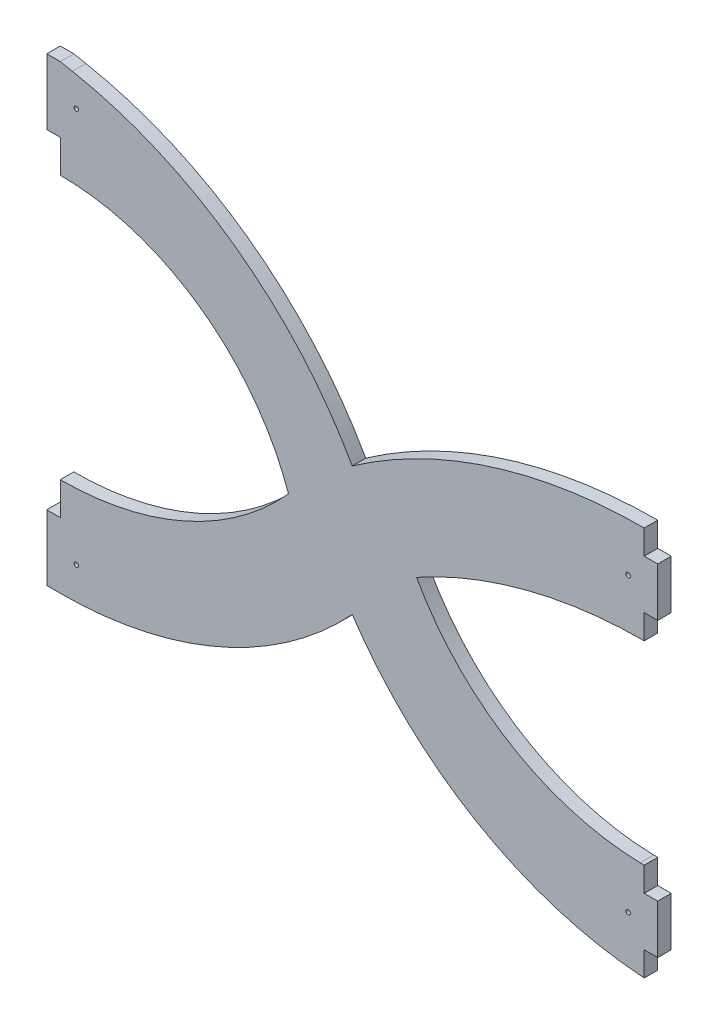
SolidWorks part; units mm, degrees
ref_plane "Front Plane" through (0, 0, 0) normal (0, 0, 1) x (1, 0, 0)
ref_plane "Top Plane" through (0, 0, 0) normal (0, 1, 0) x (1, 0, 0)
ref_plane "Right Plane" through (0, 0, 0) normal (1, 0, 0) x (0, 0, -1)
sketch "Sketch1" plane through (0, 0, 0) normal (0, 0, 1) x (1, 0, 0)
  line L1 (-141.9798, 90.4351) -> (99.3202, 90.4351)
  line L2 (-141.9798, 90.4351) -> (-141.9798, -107.6849)
  line L3 (-141.9798, -107.6849) -> (99.3202, -107.6849)
  line L4 (99.3202, 90.4351) -> (99.3202, -107.6849)
  dimension "D1" = 241.3
  dimension "D2" = 198.12
extrude "Boss-Extrude1" add sketch "Sketch1" along normal blind 5.334
sketch "Sketch2" plane through (0, 0, 5.334) normal (0, 0, 1) x (1, 0, 0)
  line L0 (99.3202, -107.6849) -> (99.3202, 90.4351) construction
  line L1 (99.3202, -107.6849) -> (93.9862, -107.6849)
  line L2 (99.3202, -107.6849) -> (99.3202, -98.0329)
  line L3 (99.3202, -98.0329) -> (93.9862, -98.0329)
  line L4 (93.9862, -107.6849) -> (93.9862, -98.0329)
  line L5 (99.3202, -78.7289) -> (93.9862, -78.7289)
  line L7 (93.9862, 17.2831) -> (99.3202, 17.2831)
  line L8 (93.9862, 17.2831) -> (93.9862, -78.7289)
  line L9 (93.9862, 36.5871) -> (93.9862, 17.2831) construction
  line L10 (99.3202, 90.4351) -> (93.9862, 90.4351)
  line L11 (99.3202, 90.4351) -> (99.3202, 36.5871)
  line L12 (99.3202, 36.5871) -> (93.9862, 36.5871)
  line L13 (93.9862, 90.4351) -> (93.9862, 36.5871)
  line L16 (99.3202, 17.2831) -> (99.3202, -78.7289)
  line L18 (93.9862, -78.7289) -> (93.9862, -98.0329) construction
  dimension "D1" = 5.334
  dimension "D3" = 19.304
  dimension "D4" = 9.652
  dimension "D5" = 19.304
  dimension "D2" = 96.012
extrude "Cut-Extrude1" cut sketch "Sketch2" against normal through all
sketch "Sketch3" plane through (0, 0, 5.334) normal (0, 0, 1) x (1, 0, 0)
  line L1 (-141.9798, -107.6849) -> (-136.6458, -107.6849)
  line L2 (-141.9798, -107.6849) -> (-141.9798, -91.4289)
  line L3 (-141.9798, -91.4289) -> (-136.6458, -91.4289)
  line L4 (-136.6458, -107.6849) -> (-136.6458, -91.4289)
  line L5 (-141.9798, 90.4351) -> (-141.9798, -107.6849) construction
  line L6 (-136.6458, -65.5209) -> (-141.9798, -65.5209)
  line L7 (-136.6458, -65.5209) -> (-136.6458, 64.5271)
  line L8 (-136.6458, 64.5271) -> (-141.9798, 64.5271)
  line L9 (-141.9798, -65.5209) -> (-141.9798, 64.5271)
  line L10 (-136.6458, -65.5209) -> (-136.6458, -91.4289) construction
  line L11 (-136.6458, 64.5271) -> (-136.6458, 90.4351) construction
  line L12 (93.9862, 90.4351) -> (-141.9798, 90.4351) construction
  dimension "D1" = 16.256
  dimension "D2" = 25.908
  dimension "D3" = 25.908
  dimension "D4" = 5.334
extrude "Cut-Extrude2" cut sketch "Sketch3" against normal through all
sketch "Sketch5" plane through (0, 0, 5.334) normal (0, 0, 1) x (1, 0, 0)
  line L0 (-136.6458, -91.4289) -> (93.9862, -107.6849) construction
  line L1 (-136.6458, -91.4289) -> (93.9862, -107.6849)
  line L2 (-136.6458, -91.4289) -> (-136.6458, -146.6044)
  line L3 (93.9862, -107.6849) -> (93.9862, -162.8604)
  line L4 (-136.6458, -146.6044) -> (93.9862, -162.8604)
extrude "Cut-Extrude5" cut sketch "Sketch5" against normal through all
sketch "Sketch6" plane through (0, 0, 5.334) normal (0, 0, 1) x (1, 0, 0)
  line L0 (-136.6458, 64.5271) -> (-136.6458, 90.4351) construction
  line L1 (93.9862, 90.4351) -> (-141.9798, 90.4351) construction
  line L2 (93.9862, 36.5871) -> (93.9862, 46.2391) construction
  line L3 (93.9862, 90.4351) -> (93.9862, 36.5871) construction
  line L4 (-136.6458, 90.4351) -> (93.9862, 46.2391)
  line L5 (-136.6458, 90.4351) -> (-136.6458, 134.6311)
  line L6 (93.9862, 46.2391) -> (93.9862, 90.4351)
  line L7 (-136.6458, 134.6311) -> (93.9862, 90.4351)
  dimension "D1" = 9.652
extrude "Cut-Extrude6" cut sketch "Sketch6" against normal through all
sketch "Sketch7" plane through (0, 0, 5.334) normal (0, 0, 1) x (1, 0, 0)
  line L0 (-21.3298, 68.3371) -> (-21.3298, -99.5569) construction
  line L1 (-136.6458, 90.4351) -> (93.9862, 46.2391) construction
  line L2 (93.9862, -107.6849) -> (-136.6458, -91.4289) construction
  line L3 (93.9862, -30.7229) -> (-136.6458, -0.4969) construction
  line L4 (93.9862, 17.2831) -> (93.9862, -78.7289) construction
  line L5 (-136.6458, -65.5209) -> (-136.6458, 64.5271) construction
  line L6 (-136.6458, 64.5271) -> (-136.6458, 51.5731) construction
  line L7 (-136.6458, -65.5209) -> (-136.6458, -52.5669) construction
  line L8 (93.9862, 17.2831) -> (93.9862, 7.6311) construction
  line L9 (93.9862, -78.7289) -> (93.9862, -69.0769) construction
  line L10 (-136.6458, 64.5271) -> (-131.8569, 89.5174) construction
  line L11 (93.9862, 36.5871) -> (93.9862, 46.2391) construction
  line L12 (-131.8569, 89.5174) -> (93.9862, 46.2391)
  line L13 (-136.6458, -65.5209) -> (-136.6458, -91.4289) construction
  line L14 (93.9862, -98.0329) -> (93.3092, -107.6372) construction
  line L15 (-136.6458, -91.4289) -> (93.3092, -107.6372)
  circle A0 centre (-21.3298, -15.6099) radius 25.4 construction
  arc A1 (93.9862, 7.6311) -> (4.0702, -15.6099) centre (93.9862, -177.9253) ccw
  arc A2 (4.0702, -15.6099) -> (92.3478, -69.0769) centre (94.8631, 34.6856) ccw
  arc A3 (92.3478, -69.0769) -> (93.9862, 7.6311) centre (93.2775, -30.7253) ccw
  arc A4 (-136.6458, 51.5731) -> (-46.5144, -12.3093) centre (-136.6458, -43.9511) cw
  arc A5 (-136.6458, -52.5669) -> (-46.5144, -12.3093) centre (-136.6458, 68.4578) ccw
  arc A6 (-136.6458, 51.5731) -> (-136.6458, -52.5669) centre (-136.6458, -0.4969) ccw
  arc A7 (-131.8569, 89.5174) -> (-21.3298, 9.7901) centre (-162.2521, -69.0963) cw
  arc A8 (93.9862, 46.2391) -> (-21.3298, 9.7901) centre (93.9862, -154.4017) ccw
  arc A9 (-136.6458, -91.4289) -> (-21.3298, -41.0099) centre (-136.6458, 65.6533) ccw
  arc A10 (93.3092, -107.6372) -> (-21.3298, -41.0099) centre (103.8923, 42.5098) cw
extrude "Cut-Extrude7" cut sketch "Sketch7" against normal through all
sketch "Sketch8" plane through (0, 0, 5.334) normal (0, 0, 1) x (1, 0, 0)
  line L0 (-141.9798, 90.4351) -> (-141.9798, 64.5271) construction
  line L1 (-141.9798, 77.4811) -> (-82.7249, 77.4811) construction
  line L2 (-141.9798, 77.4811) -> (-141.9798, -78.4749) construction
  line L3 (-141.9798, -65.5209) -> (-141.9798, -91.4289) construction
  line L4 (-141.9798, -0.4969) -> (-61.4833, -0.4969) construction
  circle A0 centre (-130.2958, 77.4811) radius 0.889
  circle A1 centre (-130.2958, -78.4749) radius 0.889
  point P2 (-141.9798, 77.4811)
  dimension "D3" = 1.778
  dimension "D1" = 11.684
  dimension "D2" = 0
extrude "Cut-Extrude8" cut sketch "Sketch8" against normal through all
sketch "Sketch9" plane through (0, 0, 5.334) normal (0, 0, 1) x (1, 0, 0)
  line L0 (99.3202, 26.9351) -> (60.8503, 26.9351) construction
  line L1 (99.3202, 17.2831) -> (99.3202, 36.5871) construction
  line L2 (99.3202, -88.3809) -> (53.0576, -88.3809) construction
  line L3 (99.3202, -98.0329) -> (99.3202, -78.7289) construction
  line L4 (99.3202, 26.9351) -> (99.3202, -88.3809) construction
  line L5 (99.3202, -30.7229) -> (41.8715, -30.7229) construction
  line L6 (93.9862, 46.2391) -> (93.9862, 36.5871) construction
  circle A0 centre (87.6362, 26.9351) radius 0.889
  circle A1 centre (87.6362, -88.3809) radius 0.889
  dimension "D1" = 1.778
  dimension "D2" = 0
  dimension "D3" = 6.35
extrude "Cut-Extrude9" cut sketch "Sketch9" against normal through all
equation "\"MDF\"= .21in"
equation "\"Foamcore\"= .13in"
equation "\"Gmaterial\"= \"MDF\""
equation "\"D1@Boss-Extrude1\"=\"MDF\""
equation "\"D1@Sketch2\"=\"MDF\""
equation "\"D4@Sketch3\"=\"MDF\""
equation "\"D1@Sketch8\"=0.25+\"MDF\""
